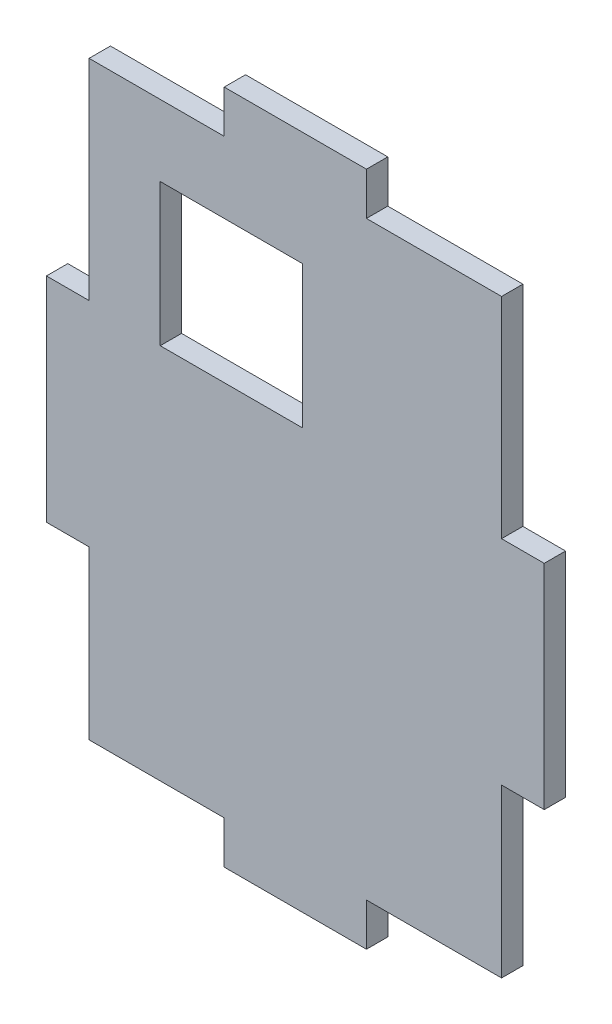
SolidWorks part; units mm, degrees
ref_plane "Plan de face" through (0, 0, 0) normal (0, 0, 1) x (1, 0, 0)
ref_plane "Plan de dessus" through (0, 0, 0) normal (0, 1, 0) x (1, 0, 0)
ref_plane "Plan de droite" through (0, 0, 0) normal (1, 0, 0) x (0, 0, -1)
sketch "Esquisse1" plane through (0, 0, 0) normal (0, 0, 1) x (1, 0, 0)
  line L1 (0, 0) -> (-70, 0)
  line L2 (0, 0) -> (0, 95)
  line L3 (0, 95) -> (-70, 95)
  line L4 (-70, 0) -> (-70, 95)
  dimension "D1" = 95
  dimension "D2" = 70
extrude "Boss.-Extru.1" add sketch "Esquisse1" along normal blind 3
sketch "Esquisse2" plane through (0, 0, 0) normal (0, 0, -1) x (-1, 0, 0)
  line L0 (0, 95) -> (70, 95) construction
  line L1 (0, 95) -> (25, 95)
  line L2 (0, 95) -> (0, 59.5)
  line L3 (6, 89) -> (25, 89)
  line L4 (25, 95) -> (25, 89)
  line L5 (70, 95) -> (45, 95)
  line L6 (0, 0) -> (25, 0)
  line L7 (64, 89) -> (45, 89)
  line L8 (45, 95) -> (45, 89)
  line L9 (70, 95) -> (70, 0) construction
  line L10 (45, 0) -> (70, 0)
  line L11 (70, 95) -> (70, 59.5)
  line L12 (70, 0) -> (70, 29.5)
  line L13 (0, 59.5) -> (6, 59.5)
  line L14 (6, 89) -> (6, 59.5)
  line L16 (0, 0) -> (0, 29.5)
  line L17 (0, 29.5) -> (6, 29.5)
  line L18 (6, 6) -> (6, 29.5)
  line L19 (54, 79) -> (34, 79)
  line L20 (54, 79) -> (54, 59)
  line L21 (6, 6) -> (25, 6)
  line L22 (25, 0) -> (25, 6)
  line L23 (54, 59) -> (34, 59)
  line L24 (34, 79) -> (34, 59)
  line L25 (64, 6) -> (45, 6)
  line L26 (45, 0) -> (45, 6)
  line L29 (70, 29.5) -> (64, 29.5)
  line L30 (64, 6) -> (64, 29.5)
  line L33 (70, 59.5) -> (64, 59.5)
  line L34 (64, 89) -> (64, 59.5)
  dimension "D1" = 6
  dimension "D2" = 20
  dimension "D3" = 6
  dimension "D4" = 25
  dimension "D5" = 6
  dimension "D6" = 30
  dimension "D7" = 35.5
  dimension "D8" = 6
  dimension "D9" = 6
  dimension "D10" = 6
  dimension "D11" = 29.5
  dimension "D12" = 19
  dimension "D13" = 20
  dimension "D14" = 6
  dimension "D15" = 30
  dimension "D16" = 6
  dimension "D17" = 20
  dimension "D18" = 20
  dimension "D19" = 10
  dimension "D20" = 10
extrude "Enlèv. mat.-Extru.1" cut sketch "Esquisse2" against normal through all
